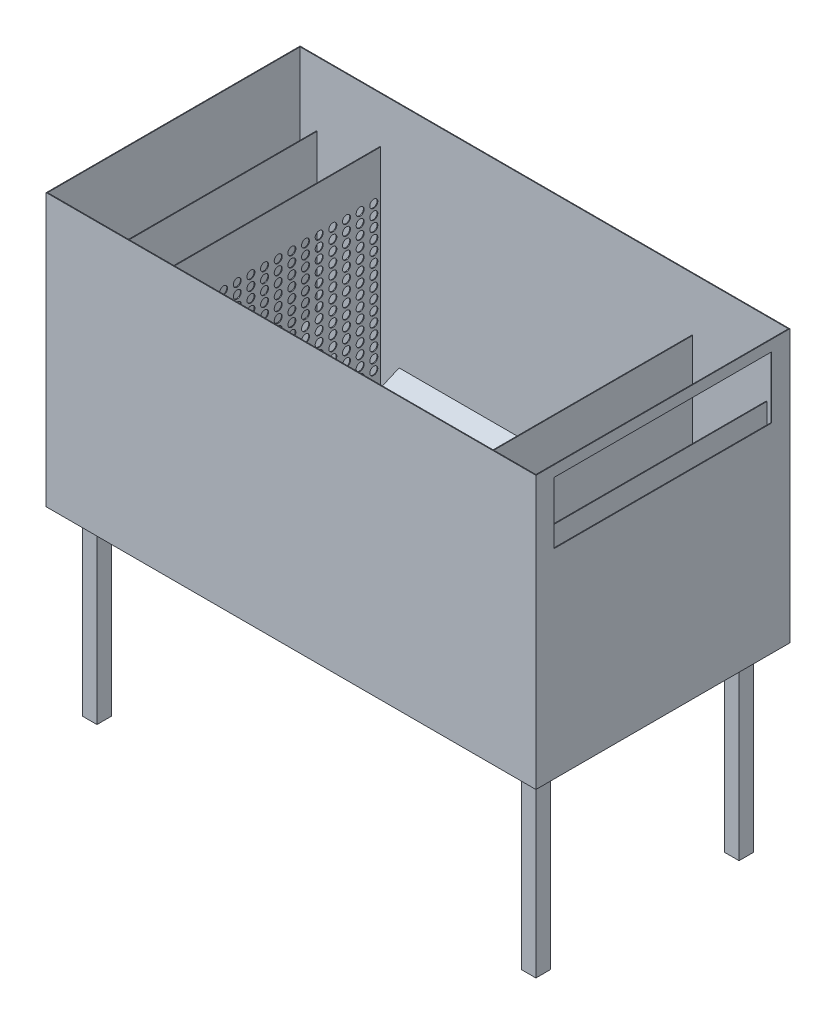
SolidWorks part; units mm, degrees
ref_plane "Спереди" through (0, 0, 0) normal (0, 0, 1) x (1, 0, 0)
ref_plane "Сверху" through (0, 0, 0) normal (0, 1, 0) x (1, 0, 0)
ref_plane "Справа" through (0, 0, 0) normal (1, 0, 0) x (0, 0, -1)
sketch "MASTER_FOOTPRINT" plane through (0, 0, 0) normal (0, 1, 0) x (1, 0, 0)
  line L1 (0, 0) -> (1350, 0)
  line L2 (0, 0) -> (0, 700)
  line L3 (0, 700) -> (1350, 700)
  line L4 (1350, 0) -> (1350, 700)
  dimension "D1" = 1350
  dimension "D2" = 700
extrude "BATH_BASE_PLATE" add sketch "MASTER_FOOTPRINT" along normal blind 750
shell "BATH_SHELL_2MM" thickness 2
sketch "Эскиз1" plane through (0, 0, 0) normal (1, 0, 0) x (0, 0, -1)
  circle A0 centre (350, 420) radius 50
extrude "INLET_D100_OPENING" cut sketch "Эскиз1" along normal blind 10
sketch "Эскиз2" plane through (0, 0, 0) normal (1, 0, 0) x (0, 0, -1)
  line L1 (80, 220) -> (620, 220)
  line L2 (80, 220) -> (80, 650)
  line L3 (80, 650) -> (620, 650)
  line L4 (620, 220) -> (620, 650)
extrude "INLET_IMPACT_BAFFLE" add sketch "Эскиз2" along normal blind 2 from offset 125 separate body
sketch "Эскиз3" plane through (0, 0, 0) normal (1, 0, 0) x (0, 0, -1)
  line L1 (30, 2) -> (670, 2)
  line L2 (30, 2) -> (30, 650)
  line L3 (30, 650) -> (670, 650)
  line L4 (670, 2) -> (670, 650)
  circle A0 centre (48.8235, 125) radius 11
  circle A1 centre (48.8235, 153.5) radius 11
  circle A2 centre (48.8235, 182) radius 11
  circle A3 centre (48.8235, 210.5) radius 11
  circle A4 centre (48.8235, 239) radius 11
  circle A5 centre (48.8235, 267.5) radius 11
  circle A6 centre (48.8235, 296) radius 11
  circle A7 centre (48.8235, 324.5) radius 11
  circle A8 centre (48.8235, 353) radius 11
  circle A9 centre (48.8235, 381.5) radius 11
  circle A10 centre (48.8235, 410) radius 11
  circle A11 centre (48.8235, 438.5) radius 11
  circle A12 centre (48.8235, 467) radius 11
  circle A13 centre (48.8235, 495.5) radius 11
  circle A14 centre (48.8235, 524) radius 11
  circle A15 centre (86.4706, 125) radius 11
  circle A16 centre (86.4706, 153.5) radius 11
  circle A17 centre (86.4706, 182) radius 11
  circle A18 centre (86.4706, 210.5) radius 11
  circle A19 centre (86.4706, 239) radius 11
  circle A20 centre (86.4706, 267.5) radius 11
  circle A21 centre (86.4706, 296) radius 11
  circle A22 centre (86.4706, 324.5) radius 11
  circle A23 centre (86.4706, 353) radius 11
  circle A24 centre (86.4706, 381.5) radius 11
  circle A25 centre (86.4706, 410) radius 11
  circle A26 centre (86.4706, 438.5) radius 11
  circle A27 centre (86.4706, 467) radius 11
  circle A28 centre (86.4706, 495.5) radius 11
  circle A29 centre (86.4706, 524) radius 11
  circle A30 centre (124.1176, 125) radius 11
  circle A31 centre (124.1176, 153.5) radius 11
  circle A32 centre (124.1176, 182) radius 11
  circle A33 centre (124.1176, 210.5) radius 11
  circle A34 centre (124.1176, 239) radius 11
  circle A35 centre (124.1176, 267.5) radius 11
  circle A36 centre (124.1176, 296) radius 11
  circle A37 centre (124.1176, 324.5) radius 11
  circle A38 centre (124.1176, 353) radius 11
  circle A39 centre (124.1176, 381.5) radius 11
  circle A40 centre (124.1176, 410) radius 11
  circle A41 centre (124.1176, 438.5) radius 11
  circle A42 centre (124.1176, 467) radius 11
  circle A43 centre (124.1176, 495.5) radius 11
  circle A44 centre (124.1176, 524) radius 11
  circle A45 centre (161.7647, 125) radius 11
  circle A46 centre (161.7647, 153.5) radius 11
  circle A47 centre (161.7647, 182) radius 11
  circle A48 centre (161.7647, 210.5) radius 11
  circle A49 centre (161.7647, 239) radius 11
  circle A50 centre (161.7647, 267.5) radius 11
  circle A51 centre (161.7647, 296) radius 11
  circle A52 centre (161.7647, 324.5) radius 11
  circle A53 centre (161.7647, 353) radius 11
  circle A54 centre (161.7647, 381.5) radius 11
  circle A55 centre (161.7647, 410) radius 11
  circle A56 centre (161.7647, 438.5) radius 11
  circle A57 centre (161.7647, 467) radius 11
  circle A58 centre (161.7647, 495.5) radius 11
  circle A59 centre (161.7647, 524) radius 11
  circle A60 centre (199.4118, 125) radius 11
  circle A61 centre (199.4118, 153.5) radius 11
  circle A62 centre (199.4118, 182) radius 11
  circle A63 centre (199.4118, 210.5) radius 11
  circle A64 centre (199.4118, 239) radius 11
  circle A65 centre (199.4118, 267.5) radius 11
  circle A66 centre (199.4118, 296) radius 11
  circle A67 centre (199.4118, 324.5) radius 11
  circle A68 centre (199.4118, 353) radius 11
  circle A69 centre (199.4118, 381.5) radius 11
  circle A70 centre (199.4118, 410) radius 11
  circle A71 centre (199.4118, 438.5) radius 11
  circle A72 centre (199.4118, 467) radius 11
  circle A73 centre (199.4118, 495.5) radius 11
  circle A74 centre (199.4118, 524) radius 11
  circle A75 centre (237.0588, 125) radius 11
  circle A76 centre (237.0588, 153.5) radius 11
  circle A77 centre (237.0588, 182) radius 11
  circle A78 centre (237.0588, 210.5) radius 11
  circle A79 centre (237.0588, 239) radius 11
  circle A80 centre (237.0588, 267.5) radius 11
  circle A81 centre (237.0588, 296) radius 11
  circle A82 centre (237.0588, 324.5) radius 11
  circle A83 centre (237.0588, 353) radius 11
  circle A84 centre (237.0588, 381.5) radius 11
  circle A85 centre (237.0588, 410) radius 11
  circle A86 centre (237.0588, 438.5) radius 11
  circle A87 centre (237.0588, 467) radius 11
  circle A88 centre (237.0588, 495.5) radius 11
  circle A89 centre (237.0588, 524) radius 11
  circle A90 centre (274.7059, 125) radius 11
  circle A91 centre (274.7059, 153.5) radius 11
  circle A92 centre (274.7059, 182) radius 11
  circle A93 centre (274.7059, 210.5) radius 11
  circle A94 centre (274.7059, 239) radius 11
  circle A95 centre (274.7059, 267.5) radius 11
  circle A96 centre (274.7059, 296) radius 11
  circle A97 centre (274.7059, 324.5) radius 11
  circle A98 centre (274.7059, 353) radius 11
  circle A99 centre (274.7059, 381.5) radius 11
  circle A100 centre (274.7059, 410) radius 11
  circle A101 centre (274.7059, 438.5) radius 11
  circle A102 centre (274.7059, 467) radius 11
  circle A103 centre (274.7059, 495.5) radius 11
  circle A104 centre (274.7059, 524) radius 11
  circle A105 centre (312.3529, 125) radius 11
  circle A106 centre (312.3529, 153.5) radius 11
  circle A107 centre (312.3529, 182) radius 11
  circle A108 centre (312.3529, 210.5) radius 11
  circle A109 centre (312.3529, 239) radius 11
  circle A110 centre (312.3529, 267.5) radius 11
  circle A111 centre (312.3529, 296) radius 11
  circle A112 centre (312.3529, 324.5) radius 11
  circle A113 centre (312.3529, 353) radius 11
  circle A114 centre (312.3529, 381.5) radius 11
  circle A115 centre (312.3529, 410) radius 11
  circle A116 centre (312.3529, 438.5) radius 11
  circle A117 centre (312.3529, 467) radius 11
  circle A118 centre (312.3529, 495.5) radius 11
  circle A119 centre (312.3529, 524) radius 11
  circle A120 centre (350, 125) radius 11
  circle A121 centre (350, 153.5) radius 11
  circle A122 centre (350, 182) radius 11
  circle A123 centre (350, 210.5) radius 11
  circle A124 centre (350, 239) radius 11
  circle A125 centre (350, 267.5) radius 11
  circle A126 centre (350, 296) radius 11
  circle A127 centre (350, 324.5) radius 11
  circle A128 centre (350, 353) radius 11
  circle A129 centre (350, 381.5) radius 11
  circle A130 centre (350, 410) radius 11
  circle A131 centre (350, 438.5) radius 11
  circle A132 centre (350, 467) radius 11
  circle A133 centre (350, 495.5) radius 11
  circle A134 centre (350, 524) radius 11
  circle A135 centre (387.6471, 125) radius 11
  circle A136 centre (387.6471, 153.5) radius 11
  circle A137 centre (387.6471, 182) radius 11
  circle A138 centre (387.6471, 210.5) radius 11
  circle A139 centre (387.6471, 239) radius 11
  circle A140 centre (387.6471, 267.5) radius 11
  circle A141 centre (387.6471, 296) radius 11
  circle A142 centre (387.6471, 324.5) radius 11
  circle A143 centre (387.6471, 353) radius 11
  circle A144 centre (387.6471, 381.5) radius 11
  circle A145 centre (387.6471, 410) radius 11
  circle A146 centre (387.6471, 438.5) radius 11
  circle A147 centre (387.6471, 467) radius 11
  circle A148 centre (387.6471, 495.5) radius 11
  circle A149 centre (387.6471, 524) radius 11
  circle A150 centre (425.2941, 125) radius 11
  circle A151 centre (425.2941, 153.5) radius 11
  circle A152 centre (425.2941, 182) radius 11
  circle A153 centre (425.2941, 210.5) radius 11
  circle A154 centre (425.2941, 239) radius 11
  circle A155 centre (425.2941, 267.5) radius 11
  circle A156 centre (425.2941, 296) radius 11
  circle A157 centre (425.2941, 324.5) radius 11
  circle A158 centre (425.2941, 353) radius 11
  circle A159 centre (425.2941, 381.5) radius 11
  circle A160 centre (425.2941, 410) radius 11
  circle A161 centre (425.2941, 438.5) radius 11
  circle A162 centre (425.2941, 467) radius 11
  circle A163 centre (425.2941, 495.5) radius 11
  circle A164 centre (425.2941, 524) radius 11
  circle A165 centre (462.9412, 125) radius 11
  circle A166 centre (462.9412, 153.5) radius 11
  circle A167 centre (462.9412, 182) radius 11
  circle A168 centre (462.9412, 210.5) radius 11
  circle A169 centre (462.9412, 239) radius 11
  circle A170 centre (462.9412, 267.5) radius 11
  circle A171 centre (462.9412, 296) radius 11
  circle A172 centre (462.9412, 324.5) radius 11
  circle A173 centre (462.9412, 353) radius 11
  circle A174 centre (462.9412, 381.5) radius 11
  circle A175 centre (462.9412, 410) radius 11
  circle A176 centre (462.9412, 438.5) radius 11
  circle A177 centre (462.9412, 467) radius 11
  circle A178 centre (462.9412, 495.5) radius 11
  circle A179 centre (462.9412, 524) radius 11
  circle A180 centre (500.5882, 125) radius 11
  circle A181 centre (500.5882, 153.5) radius 11
  circle A182 centre (500.5882, 182) radius 11
  circle A183 centre (500.5882, 210.5) radius 11
  circle A184 centre (500.5882, 239) radius 11
  circle A185 centre (500.5882, 267.5) radius 11
  circle A186 centre (500.5882, 296) radius 11
  circle A187 centre (500.5882, 324.5) radius 11
  circle A188 centre (500.5882, 353) radius 11
  circle A189 centre (500.5882, 381.5) radius 11
  circle A190 centre (500.5882, 410) radius 11
  circle A191 centre (500.5882, 438.5) radius 11
  circle A192 centre (500.5882, 467) radius 11
  circle A193 centre (500.5882, 495.5) radius 11
  circle A194 centre (500.5882, 524) radius 11
  circle A195 centre (538.2353, 125) radius 11
  circle A196 centre (538.2353, 153.5) radius 11
  circle A197 centre (538.2353, 182) radius 11
  circle A198 centre (538.2353, 210.5) radius 11
  circle A199 centre (538.2353, 239) radius 11
  circle A200 centre (538.2353, 267.5) radius 11
  circle A201 centre (538.2353, 296) radius 11
  circle A202 centre (538.2353, 324.5) radius 11
  circle A203 centre (538.2353, 353) radius 11
  circle A204 centre (538.2353, 381.5) radius 11
  circle A205 centre (538.2353, 410) radius 11
  circle A206 centre (538.2353, 438.5) radius 11
  circle A207 centre (538.2353, 467) radius 11
  circle A208 centre (538.2353, 495.5) radius 11
  circle A209 centre (538.2353, 524) radius 11
  circle A210 centre (575.8824, 125) radius 11
  circle A211 centre (575.8824, 153.5) radius 11
  circle A212 centre (575.8824, 182) radius 11
  circle A213 centre (575.8824, 210.5) radius 11
  circle A214 centre (575.8824, 239) radius 11
  circle A215 centre (575.8824, 267.5) radius 11
  circle A216 centre (575.8824, 296) radius 11
  circle A217 centre (575.8824, 324.5) radius 11
  circle A218 centre (575.8824, 353) radius 11
  circle A219 centre (575.8824, 381.5) radius 11
  circle A220 centre (575.8824, 410) radius 11
  circle A221 centre (575.8824, 438.5) radius 11
  circle A222 centre (575.8824, 467) radius 11
  circle A223 centre (575.8824, 495.5) radius 11
  circle A224 centre (575.8824, 524) radius 11
  circle A225 centre (613.5294, 125) radius 11
  circle A226 centre (613.5294, 153.5) radius 11
  circle A227 centre (613.5294, 182) radius 11
  circle A228 centre (613.5294, 210.5) radius 11
  circle A229 centre (613.5294, 239) radius 11
  circle A230 centre (613.5294, 267.5) radius 11
  circle A231 centre (613.5294, 296) radius 11
  circle A232 centre (613.5294, 324.5) radius 11
  circle A233 centre (613.5294, 353) radius 11
  circle A234 centre (613.5294, 381.5) radius 11
  circle A235 centre (613.5294, 410) radius 11
  circle A236 centre (613.5294, 438.5) radius 11
  circle A237 centre (613.5294, 467) radius 11
  circle A238 centre (613.5294, 495.5) radius 11
  circle A239 centre (613.5294, 524) radius 11
  circle A240 centre (651.1765, 125) radius 11
  circle A241 centre (651.1765, 153.5) radius 11
  circle A242 centre (651.1765, 182) radius 11
  circle A243 centre (651.1765, 210.5) radius 11
  circle A244 centre (651.1765, 239) radius 11
  circle A245 centre (651.1765, 267.5) radius 11
  circle A246 centre (651.1765, 296) radius 11
  circle A247 centre (651.1765, 324.5) radius 11
  circle A248 centre (651.1765, 353) radius 11
  circle A249 centre (651.1765, 381.5) radius 11
  circle A250 centre (651.1765, 410) radius 11
  circle A251 centre (651.1765, 438.5) radius 11
  circle A252 centre (651.1765, 467) radius 11
  circle A253 centre (651.1765, 495.5) radius 11
  circle A254 centre (651.1765, 524) radius 11
extrude "DISTRIBUTOR_D22" add sketch "Эскиз3" along normal blind 2 from offset 250 separate body
sketch "Эскиз4" plane through (0, 0, 0) normal (1, 0, 0) x (0, 0, -1)
  line L1 (50, 320) -> (650, 320)
  line L2 (50, 320) -> (50, 650)
  line L3 (50, 650) -> (650, 650)
  line L4 (650, 320) -> (650, 650)
extrude "OUTLET_SUBMERGED_BAFFLE" add sketch "Эскиз4" along normal blind 2 from offset 1130 separate body
sketch "Эскиз5" plane through (0, 0, 0) normal (1, 0, 0) x (0, 0, -1)
  line L1 (5, 2) -> (695, 2)
  line L2 (5, 2) -> (5, 550)
  line L3 (5, 550) -> (695, 550)
  line L4 (695, 2) -> (695, 550)
extrude "OVERFLOW_WEIR_Z550" add sketch "Эскиз5" along normal blind 2 from offset 1290 separate body
sketch "Эскиз6" plane through (0, 0, 0) normal (1, 0, 0) x (0, 0, -1)
  line L1 (50, 550) -> (650, 550)
  line L2 (50, 550) -> (50, 720)
  line L3 (50, 720) -> (650, 720)
  line L4 (650, 550) -> (650, 720)
extrude "OUTLET_WEIR_SLOT_W600" cut sketch "Эскиз6" along normal blind 10 from offset 1345
sketch "Эскиз7" plane through (0, 0, 0) normal (1, 0, 0) x (0, 0, -1)
  line L0 (2, -1) -> (2, 120)
  line L1 (2, 120) -> (280, -1)
  line L2 (280, -1) -> (2, -1)
  line L3 (698, -1) -> (698, 120)
  line L4 (698, 120) -> (420, -1)
  line L5 (420, -1) -> (698, -1)
extrude "SLOPED_SEDIMENT_FLOOR" add sketch "Эскиз7" along normal blind 825 from offset 275
sketch3d "SCREW_AXIS_30DEG_REFERENCE"
  line L0 (400, 70, -350) -> (1450, 676.2178, -350)
sketch "Эскиз8" plane through (0, 0, 0) normal (0, 1, 0) x (1, 0, 0)
  line L1 (50, 50) -> (90, 50)
  line L2 (50, 50) -> (50, 90)
  line L3 (50, 90) -> (90, 90)
  line L4 (90, 50) -> (90, 90)
  line L6 (50, 610) -> (90, 610)
  line L7 (50, 610) -> (50, 650)
  line L8 (50, 650) -> (90, 650)
  line L9 (90, 610) -> (90, 650)
  line L11 (1260, 50) -> (1300, 50)
  line L12 (1260, 50) -> (1260, 90)
  line L13 (1260, 90) -> (1300, 90)
  line L14 (1300, 50) -> (1300, 90)
  line L16 (1260, 610) -> (1300, 610)
  line L17 (1260, 610) -> (1260, 650)
  line L18 (1260, 650) -> (1300, 650)
  line L19 (1300, 610) -> (1300, 650)
extrude "FRAME_FOUR_LEGS_40X40" add sketch "Эскиз8" against normal blind 500
equation "\"AI_Q_Peak\"= 0.006"
equation "\"AI_B_Bath\"= 700"
equation "\"AI_L_Settle\"= 900"
equation "\"AI_L_Inlet\"= 250"
equation "\"AI_L_Outlet\"= 200"
equation "\"AI_L_Bath\"= 1350"
equation "\"AI_H_Water\"= 550"
equation "\"AI_H_Freeboard\"= 200"
equation "\"AI_H_Bath\"= 750"
equation "\"AI_Shell_Thickness\"= 2"
equation "\"AI_Inlet_DN\"= 100"
equation "\"AI_Weir_Width\"= 600"
equation "\"AI_Inlet_Baffle_Offset\"= 125"
equation "\"AI_Distributor_Open_Area\"= 0.28"
equation "\"AI_Distributor_Hole_Dia\"= 22"
equation "\"AI_Distributor_Blind_Zone\"= 110"
equation "\"AI_Outlet_Baffle_Depth\"= 250"
equation "\"AI_Screw_Diameter\"= 100"
equation "\"AI_Screw_Pitch\"= 100"
equation "\"AI_Screw_Angle\"= 30"
equation "\"AI_Screw_Rpm\"= 15"
equation "\"AI_Screw_Clearance\"= 5"
equation "\"AI_Liner_Thickness\"= 5"
equation "\"AI_Discharge_Height\"= 650"
equation "\"AI_Frame_Height\"= 500"
equation "\"D1@MASTER_FOOTPRINT\" = \"AI_L_Bath\""
equation "\"D2@MASTER_FOOTPRINT\" = \"AI_B_Bath\""
equation "\"D1@BATH_BASE_PLATE\" = \"AI_H_Bath\""
